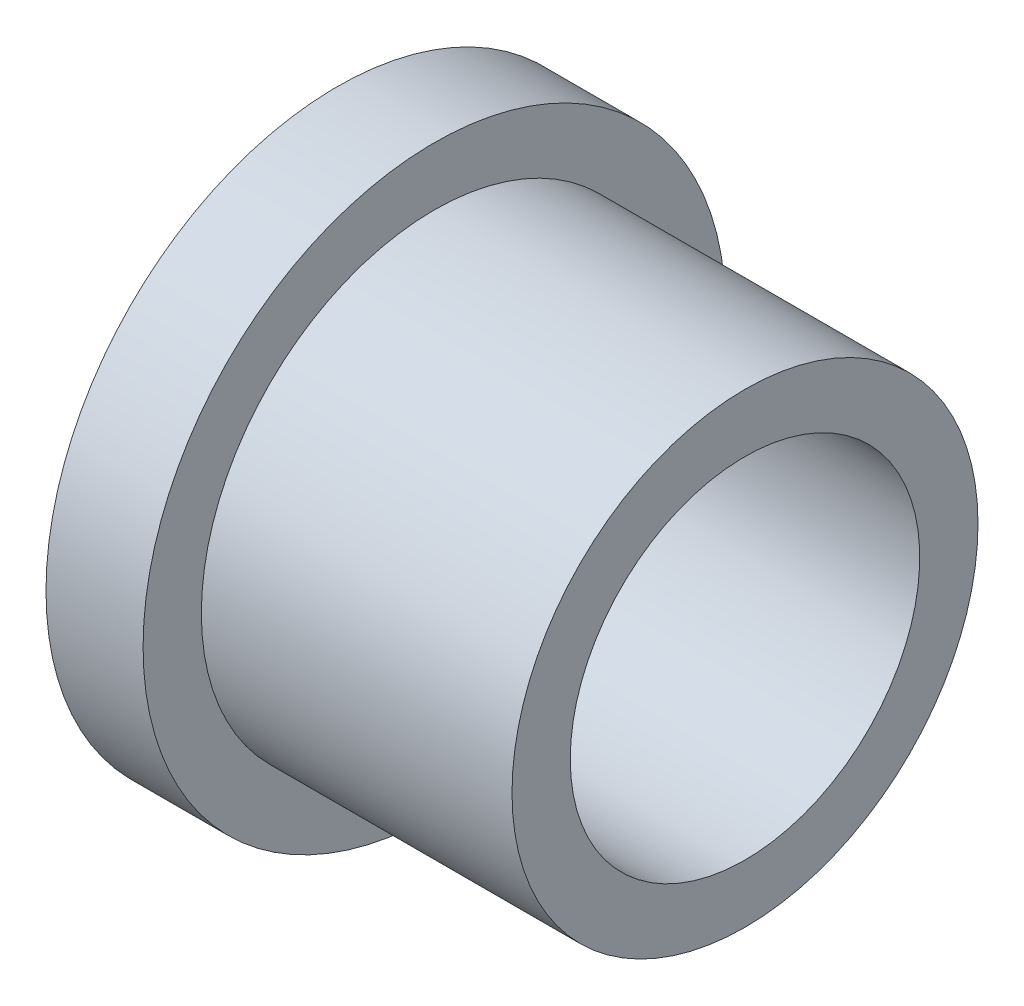
SolidWorks part; units mm, degrees
ref_plane "Front Plane" through (0, 0, 0) normal (0, 0, 1) x (1, 0, 0)
ref_plane "Top Plane" through (0, 0, 0) normal (0, 1, 0) x (1, 0, 0)
ref_plane "Right Plane" through (0, 0, 0) normal (1, 0, 0) x (0, 0, -1)
sketch "Sketch1" plane through (0, 0, 0) normal (0, 0, 1) x (1, 0, 0)
  line L0 (-10.5, 0) -> (16.9433, 0) construction
  line L1 (-10.5, 9) -> (-10.5, 15)
  line L2 (-10.5, 15) -> (-5.5, 15)
  line L3 (-5.5, 15) -> (-5.5, 12)
  line L4 (-5.5, 12) -> (10.5, 12)
  line L5 (10.5, 12) -> (10.5, 9)
  line L6 (10.5, 9) -> (-10.5, 9)
  dimension "D1" = 12
  dimension "D2" = 15
  dimension "D3" = 10.5
  dimension "D4" = 10.5
  dimension "D5" = 16
  dimension "D6" = 3
revolve "Revolve1" add sketch "Sketch1" angle 360 about L0
